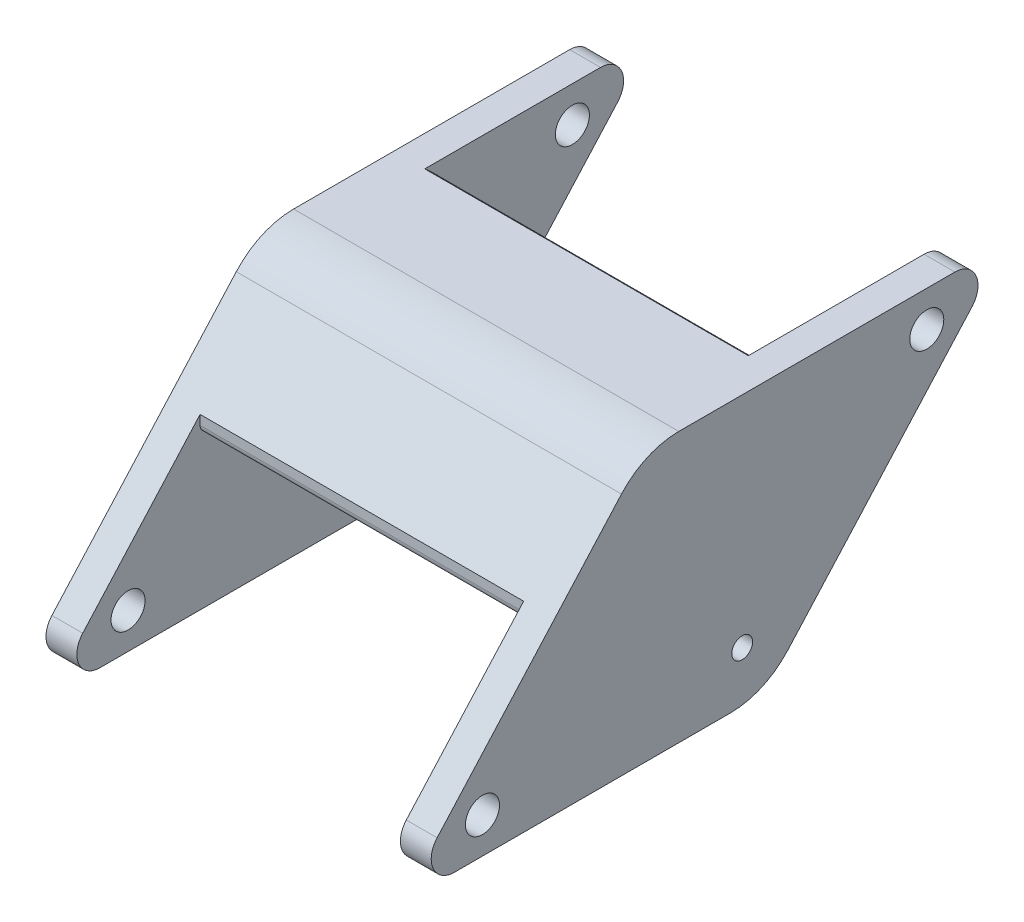
SolidWorks part; units mm, degrees
ref_plane "Front Plane" through (0, 0, 0) normal (0, 0, 1) x (1, 0, 0)
ref_plane "Top Plane" through (0, 0, 0) normal (0, 1, 0) x (1, 0, 0)
ref_plane "Right Plane" through (0, 0, 0) normal (1, 0, 0) x (0, 0, -1)
sketch "Sketch4" plane through (0, 0, 0) normal (1, 0, 0) x (0, 0, -1)
  line L4 (-14.0132, 16.5502) -> (21.8223, 16.5502)
  line L5 (-21.4568, 13.228) -> (-45.3869, -13.4464)
  line L6 (24.0553, 11.5469) -> (0.1252, -15.1276)
  line L7 (-43.1539, -18.4498) -> (-7.3184, -18.4498)
  line L8 (28.5439, 16.5502) -> (-49.8755, -18.4498) construction
  line L9 (-18.4764, 16.5502) -> (-2.8552, -18.4498) construction
  circle A0 centre (-5.9527, -11.5096) radius 3.6
  arc A1 (-7.3184, -18.4498) -> (0.1252, -15.1276) centre (-7.3184, -8.4498) ccw
  arc A2 (-45.3869, -13.4464) -> (-43.1539, -18.4498) centre (-43.1539, -15.4498) ccw
  arc A3 (24.0553, 11.5469) -> (21.8223, 16.5502) centre (21.8223, 13.5502) ccw
  arc A4 (-21.4568, 13.228) -> (-14.0132, 16.5502) centre (-14.0132, 6.5502) cw
  dimension "D3" = 7.2
  dimension "D5" = 10
  dimension "D6" = 3
  dimension "D7" = 3
  dimension "D8" = 10
  dimension "D1" = 35
  dimension "D2" = 35
  dimension "D4" = 7.6
extrude "ThickBase" add sketch "Sketch4" along normal blind 4
sketch "Sketch5" plane through (4, 0, 0) normal (1, 0, 0) x (0, 0, -1)
  line L0 (-43.1539, -18.4498) -> (-7.3184, -18.4498) construction
  line L1 (0.1252, -15.1276) -> (24.0553, 11.5469) construction
  line L2 (15.9453, 2.5068) -> (24.0553, 11.5469)
  line L3 (21.8223, 16.5502) -> (-14.0132, 16.5502)
  line L4 (21.8223, 16.5502) -> (-14.0132, 16.5502) construction
  line L5 (-21.4568, 13.228) -> (-45.3869, -13.4464)
  line L6 (-43.1539, -18.4498) -> (-31.0091, -18.4498)
  circle A0 centre (-5.9527, -11.5096) radius 24 construction
  arc A1 (-31.0091, -18.4498) -> (15.9453, 2.5068) centre (-5.9527, -11.5096) cw
  arc A2 (-43.1539, -18.4498) -> (-45.3869, -13.4464) centre (-43.1539, -15.4498) cw
  arc A3 (-45.3869, -13.4464) -> (-43.1539, -18.4498) centre (-43.1539, -15.4498) ccw construction
  arc A4 (24.0553, 11.5469) -> (21.8223, 16.5502) centre (21.8223, 13.5502) ccw
  arc A5 (24.0553, 11.5469) -> (21.8223, 16.5502) centre (21.8223, 13.5502) ccw construction
  arc A6 (-14.0132, 16.5502) -> (-21.4568, 13.228) centre (-14.0132, 6.5502) ccw
  arc A7 (-14.0132, 16.5502) -> (-21.4568, 13.228) centre (-14.0132, 6.5502) ccw construction
  dimension "D1" = 25.9997
extrude "Middle" add sketch "Sketch5" along normal blind 42
sketch "Sketch7" plane through (46, 0, 0) normal (1, 0, 0) x (0, 0, -1)
  line L0 (-45.3869, -13.4464) -> (-21.4568, 13.228)
  line L1 (-14.0132, 16.5502) -> (21.8223, 16.5502)
  line L7 (0.1252, -15.1276) -> (24.0553, 11.5469)
  line L8 (-7.3184, -18.4498) -> (-43.1539, -18.4498)
  arc A0 (-43.1539, -18.4498) -> (-45.3869, -13.4464) centre (-43.1539, -15.4498) cw
  arc A1 (-45.3869, -13.4464) -> (-43.1539, -18.4498) centre (-43.1539, -15.4498) ccw construction
  arc A2 (-21.4568, 13.228) -> (-14.0132, 16.5502) centre (-14.0132, 6.5502) cw
  arc A3 (-14.0132, 16.5502) -> (-21.4568, 13.228) centre (-14.0132, 6.5502) ccw construction
  arc A4 (21.8223, 16.5502) -> (24.0553, 11.5469) centre (21.8223, 13.5502) cw
  arc A5 (24.0553, 11.5469) -> (21.8223, 16.5502) centre (21.8223, 13.5502) ccw construction
  arc A9 (0.1252, -15.1276) -> (-7.3184, -18.4498) centre (-7.3184, -8.4498) cw
  arc M3 (-31.0091, -18.4498) -> (15.9453, 2.5068) centre (-5.9527, -11.5096) cw
  line M4 (15.9453, 2.5068) -> (24.0553, 11.5469)
  arc M5 (24.0553, 11.5469) -> (21.8223, 16.5502) centre (21.8223, 13.5502) ccw
  line M6 (21.8223, 16.5502) -> (-14.0132, 16.5502)
  arc M7 (-14.0132, 16.5502) -> (-21.4568, 13.228) centre (-14.0132, 6.5502) ccw
  line M8 (-21.4568, 13.228) -> (-45.3869, -13.4464)
  arc M9 (-45.3869, -13.4464) -> (-43.1539, -18.4498) centre (-43.1539, -15.4498) ccw
  line M10 (-43.1539, -18.4498) -> (-31.0091, -18.4498)
extrude "ThinBase" add sketch "Sketch7" along normal blind 4 contours A9 L7 L8 M3 | M10 M3 M4 M5 M6 M7 M8 M9
sketch "Sketch8" plane through (50, 0, 0) normal (1, 0, 0) x (0, 0, -1)
  line L0 (24.0553, 11.5469) -> (-7.2859, -23.3885) construction
  line L1 (-43.1539, -18.4498) -> (5.9786, -18.4498) construction
  line L2 (21.8223, 16.5502) -> (-40.1855, 16.5502) construction
  line L3 (-45.3869, -13.4464) -> (-21.4568, 13.228) construction
  line L4 (-21.4568, 13.228) -> (-14.3706, 21.1268) construction
  line L5 (-18.4764, 16.5502) -> (-2.8552, -18.4498) construction
  circle A0 centre (-5.7897, -11.8749) radius 1.35
  point P0 (-5.7897, -11.8749)
  point P8 (-2.8552, -18.4498)
  point P16 (-18.4764, 16.5502)
  dimension "D3" = 2.7
  dimension "D1" = 7.2
  dimension "D2" = 38.3278
extrude "RetainerScrew" cut sketch "Sketch8" against normal up to surface (4 mm away) up to face at (46, -7.5273, 7.7302)
sketch "Sketch9" plane through (46, 0, 0) normal (-1, 0, 0) x (0, 0, 1)
  circle A0 centre (5.7897, -11.8749) radius 1.35
  circle A1 centre (5.7897, -11.8749) radius 3
  dimension "D1" = 6
  dimension "D2" = 2.7
extrude "Spacer" add sketch "Sketch9" along normal blind 8.2
sketch "Sketch15" plane through (0, 16.5502, 0) normal (0, 1, 0) x (1, 0, 0)
  line L0 (4, 24.8223) -> (4, -46.1539) construction
  line L1 (50, 24.8223) -> (0, 24.8223) construction
  line L2 (0, -46.1539) -> (50, -46.1539) construction
  line L3 (46, 24.8223) -> (46, -46.1539) construction
  line L4 (50, 21.8223) -> (50, -14.0132) construction
  line L5 (0, 21.8223) -> (0, -14.0132) construction
  line L6 (25, -21.4568) -> (46, -21.4568) construction
  line L7 (50, -21.4568) -> (0, -21.4568) construction
  line L8 (25, -21.4568) -> (4, -21.4568) construction
  line L9 (4, -46.1539) -> (46, -46.1539) construction
  line L10 (4, -30.1539) -> (46, -30.1539)
  line L15 (46, -30.1539) -> (46, -46.1539)
  line L16 (46, -46.1539) -> (4, -46.1539)
  line L17 (4, -30.1539) -> (4, -46.1539)
  dimension "D1" = 4
  dimension "D2" = 4
  dimension "D3" = 16
  dimension "D4" = 42
extrude "H1" cut sketch "Sketch15" against normal through all
sketch "Sketch17" plane through (0, 16.5642, 18.4638) normal (0, 0.6678, 0.7444) x (1, 0, 0)
  line L0 (4, 27.6587) -> (4, -43.3174) construction
  line L1 (50, 27.6587) -> (0, 27.6587) construction
  line L2 (0, -43.3174) -> (4, -43.3174) construction
  line L3 (0, 26.8918) -> (0, 2.9616) construction
  line L4 (46, -43.3174) -> (46, 27.6587) construction
  line L5 (46, -43.3174) -> (50, -43.3174) construction
  line L6 (50, 26.8918) -> (50, 2.9616) construction
  line L8 (4, 27.6587) -> (46, 27.6587)
  line L9 (4, 27.6587) -> (4, 11.6587)
  line L10 (4, 11.6587) -> (46, 11.6587)
  line L11 (46, 27.6587) -> (46, 11.6587)
  dimension "D1" = 4
  dimension "D2" = 4
  dimension "D3" = 16
extrude "H2" cut sketch "Sketch17" against normal through all contours L10 L11 L8 L9
fillet "R1" radius 1 1 edges at (25, -2.0075, 30.1539)
fillet "R2" radius 1 1 edges at (25, 12.85, -3.1352)
sketch "Sketch18" plane through (50, 0, 0) normal (1, 0, 0) x (0, 0, -1)
  line L0 (-45.8934, -16.6725) -> (24.5618, 14.7729) construction
  arc A0 (-45.3869, -13.4464) -> (-43.1539, -18.4498) centre (-43.1539, -15.4498) ccw construction
  arc A1 (24.0553, 11.5469) -> (21.8223, 16.5502) centre (21.8223, 13.5502) ccw construction
  circle A2 centre (-39.5012, -13.8195) radius 2.21
  circle A3 centre (18.1696, 11.92) radius 2.21
  dimension "D1" = 7
  dimension "D2" = 4.42
  dimension "D3" = 4.42
  dimension "D4" = 7
extrude "SideScrews" cut sketch "Sketch18" against normal through all
